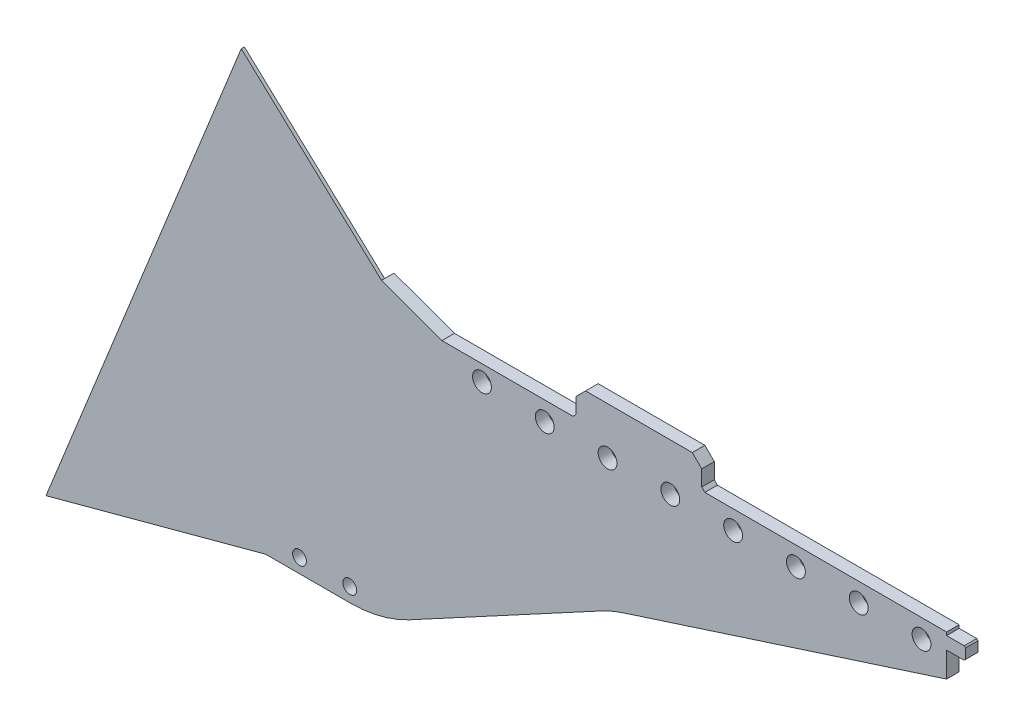
SolidWorks part; units mm, degrees
material "Thornel Mat VMA"
ref_plane "前视基准面" through (0, 0, 0) normal (0, 0, 1) x (1, 0, 0)
ref_plane "上视基准面" through (0, 0, 0) normal (0, 1, 0) x (1, 0, 0)
ref_plane "右视基准面" through (0, 0, 0) normal (1, 0, 0) x (0, 0, -1)
sketch "草图1" plane through (0, 0, 0) normal (0, 0, 1) x (1, 0, 0)
  line L0 (56.016, 19) -> (53.216, 19)
  line L1 (53.216, 19) -> (53.216, 19.5)
  line L2 (53.216, 19.5) -> (14.716, 19.5)
  line L3 (14.716, 19.5) -> (14.216, 20)
  line L4 (14.216, 20) -> (14.216, 22.5)
  line L5 (14.216, 22.5) -> (12.716, 24)
  line L6 (12.716, 24) -> (-4.284, 24)
  line L7 (-4.284, 24) -> (-5.784, 22.5)
  line L8 (-5.784, 22.5) -> (-5.784, 20)
  line L9 (-5.784, 20) -> (-6.284, 19.5)
  line L10 (-6.284, 19.5) -> (-27.159, 19.5)
  line L11 (-27.159, 19.5) -> (-36.784, 23)
  line L12 (-36.784, 23) -> (-36.784, 19)
  line L13 (-36.784, 19) -> (-56.1227, -22.5783)
  line L14 (-55.216, -24) -> (-41.8388, -24)
  line L15 (-32.3362, -21.5983) -> (-1.7443, -5.0796)
  line L16 (1.6184, -3.6437) -> (53.216, 13)
  line L17 (53.216, 13) -> (53.216, 17)
  line L18 (53.216, 17) -> (56.016, 17)
  line L19 (56.016, 17) -> (56.216, 17.2)
  line L20 (56.216, 17.2) -> (56.216, 18.8)
  line L21 (56.216, 18.8) -> (56.016, 19)
  circle A0 centre (-41.8388, -21.75) radius 1.1
  arc A1 (-56.1227, -22.5783) -> (-55.216, -24) centre (-55.216, -23) ccw
  arc A2 (-41.8388, -24) -> (-32.3362, -21.5983) centre (-41.8388, -4) ccw
  arc A3 (1.6184, -3.6437) -> (-1.7443, -5.0796) centre (7.7583, -22.6779) ccw
  circle A4 centre (-49.8388, -21.75) radius 1.1
  circle A5 centre (49.216, 16.5) radius 1.5
  circle A6 centre (39.216, 16.5) radius 1.5
  circle A7 centre (29.216, 16.5) radius 1.5
  circle A8 centre (19.216, 16.5) radius 1.5
  circle A9 centre (9.216, 16.5) radius 1.5
  circle A10 centre (-0.784, 16.5) radius 1.5
  circle A11 centre (-10.784, 16.5) radius 1.5
  circle A12 centre (-20.784, 17) radius 1.5
extrude "凸台-拉伸1" add sketch "草图1" along normal blind 2
sketch "草图2" plane through (0, 0, 2) normal (0, 0, 1) x (1, 0, 0)
  line L0 (-55.216, -24) -> (-90.216, -33.415)
  line L1 (-36.784, 19) -> (-56.1227, -22.5783) construction
  line L2 (-90.216, -33.415) -> (-59.1141, 43.7824)
  line L3 (-59.1141, 43.7824) -> (-36.784, 23)
  line L4 (-36.784, 23) -> (-36.784, 19)
  line L5 (-36.784, 19) -> (-56.1227, -22.5783)
  arc A0 (-56.1227, -22.5783) -> (-55.216, -24) centre (-55.216, -23) ccw
  point P13 (-59.2597, 43.4212)
  dimension "D1" = 130
  dimension "D2" = 53
  dimension "D3" = 108
  dimension "D4" = 35
extrude "凸台-拉伸2" add sketch "草图2" against normal blind 0.5
equation "\"50、\"=50"
